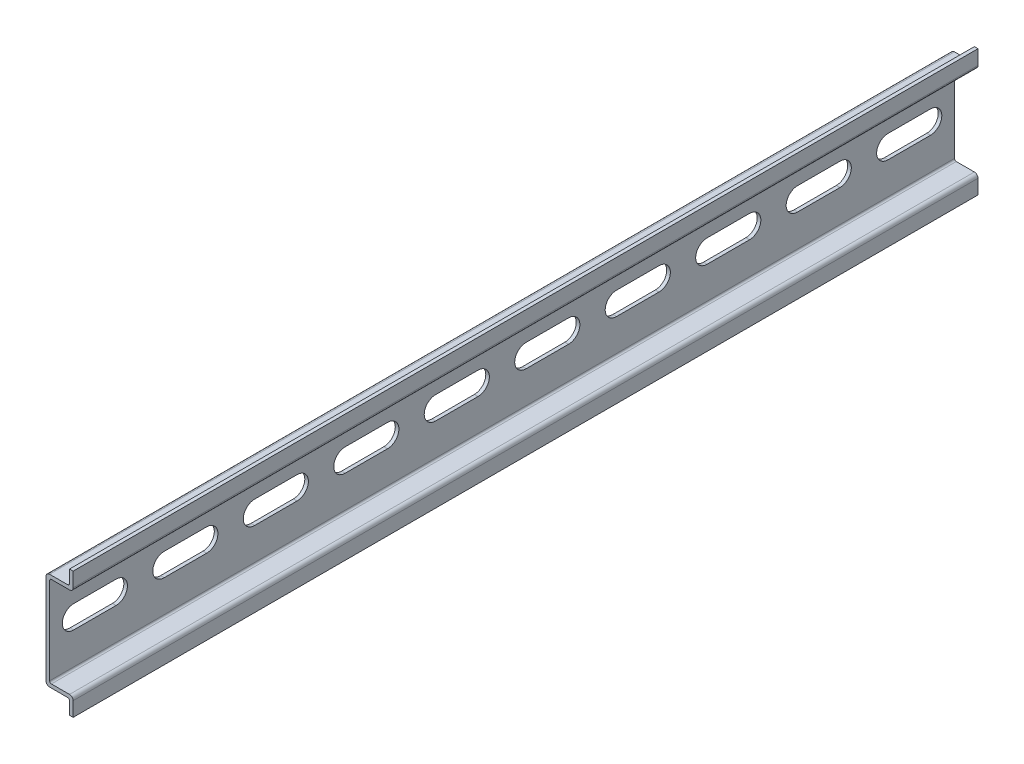
SolidWorks part; units mm, degrees
ref_plane "Front Plane" through (0, 0, 0) normal (0, 0, 1) x (1, 0, 0)
ref_plane "Top Plane" through (0, 0, 0) normal (0, 1, 0) x (1, 0, 0)
ref_plane "Right Plane" through (0, 0, 0) normal (1, 0, 0) x (0, 0, -1)
sketch "Sketch1" plane through (0, 0, 0) normal (0, 0, 1) x (1, 0, 0)
  line L0 (0, 0) -> (7.5, 0) construction
  line L1 (0, 17.5) -> (7.5, 17.5) construction
  line L2 (0, 17.5) -> (0, -17.5) construction
  line L3 (0, -17.5) -> (7.5, -17.5) construction
  line L4 (7.5, 17.5) -> (7.5, -17.5) construction
  line L5 (7.5, 17.5) -> (6.5, 17.5)
  line L6 (6.5, 17.5) -> (6.5, 14)
  line L7 (6, 13.5) -> (1, 13.5)
  line L8 (0, 12.5) -> (0, -12.5)
  line L9 (7.5, 17.5) -> (7.5, 13.5)
  line L10 (6.5, 12.5) -> (1.5, 12.5)
  line L11 (1, 12) -> (1, -12)
  line L12 (6.5, -12.5) -> (1.5, -12.5)
  line L13 (7.5, -17.5) -> (7.5, -13.5)
  line L14 (6, -13.5) -> (1, -13.5)
  line L15 (6.5, -17.5) -> (6.5, -14)
  line L16 (7.5, -17.5) -> (6.5, -17.5)
  line L17 (6.3536, 13.6464) -> (7.2071, 12.7929) construction
  line L18 (1.1464, 12.3536) -> (0.2929, 13.2071) construction
  arc A0 (1.5, 12.5) -> (1, 12) centre (1.5, 12) ccw
  arc A1 (1, 13.5) -> (0, 12.5) centre (1, 12.5) ccw
  arc A2 (7.5, 13.5) -> (6.5, 12.5) centre (6.5, 13.5) cw
  arc A3 (6, 13.5) -> (6.5, 14) centre (6, 14) ccw
  arc A4 (1, -13.5) -> (0, -12.5) centre (1, -12.5) cw
  arc A5 (1.5, -12.5) -> (1, -12) centre (1.5, -12) cw
  arc A6 (7.5, -13.5) -> (6.5, -12.5) centre (6.5, -13.5) ccw
  arc A7 (6, -13.5) -> (6.5, -14) centre (6, -14) cw
  dimension "D5" = 1
  dimension "D6" = 0.5
  dimension "D1" = 35
  dimension "D2" = 7.5
  dimension "D3" = 1
  dimension "D4" = 27
extrude "Boss-Extrude1" add sketch "Sketch1" along normal mid plane 250
sketch "Sketch2" plane through (0, 0, 0) normal (1, 0, 0) x (0, 0, -1)
  line L0 (-118.35, 0) -> (-106.65, 0) construction
  line L1 (-118.35, 3.15) -> (-106.65, 3.15)
  line L2 (-118.35, -3.15) -> (-106.65, -3.15)
  line L3 (-112.5, 0) -> (-125, 0) construction
  line L4 (-125, 12.5) -> (-125, -12.5) construction
  line L5 (-112.5, 0) -> (-87.5, 0) construction
  line L6 (-87.5, 0) -> (-62.5, 0) construction
  arc A0 (-118.35, 3.15) -> (-118.35, -3.15) centre (-118.35, 0) ccw
  arc A1 (-106.65, -3.15) -> (-106.65, 3.15) centre (-106.65, 0) ccw
  point P2 (-112.5, 0)
  dimension "D1" = 6.3
  dimension "D2" = 18
  dimension "D4" = 12.5
  dimension "D3" = 25
extrude "Cut-Extrude1" cut sketch "Sketch2" along normal up to vertex (7.5 mm away) up to point (7.5, 0, 0)
pattern_linear "LPattern1" count 10 spacing 25 along (0, 0, -1) of "Cut-Extrude1"
equation "\"D4@Sketch2\" = \"D3@Sketch2\" / 2"
equation "\"D3@LPattern1\" = \"D3@Sketch2\""
equation "\"D1@LPattern1\" = \"D1@Boss-Extrude1\" / \"D3@LPattern1\""
